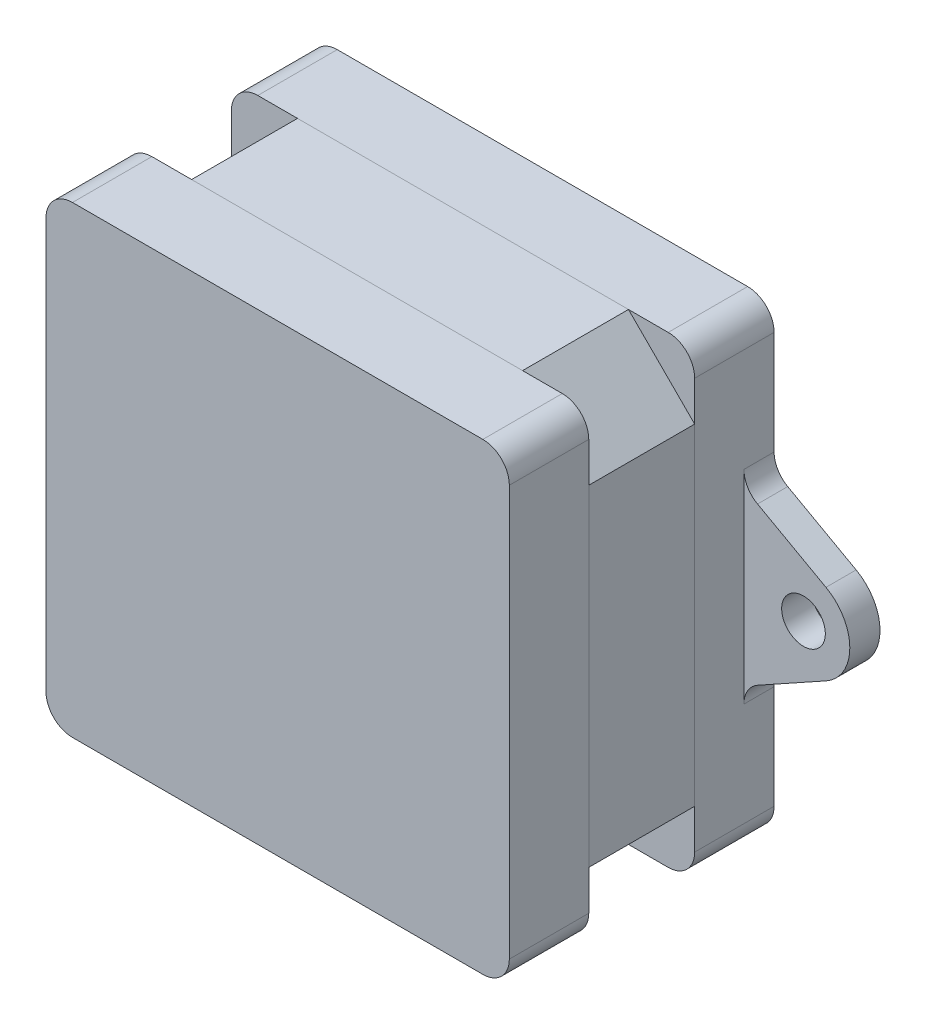
SolidWorks part; units mm, degrees
ref_plane "Front Plane" through (0, 0, 0) normal (0, 0, 1) x (1, 0, 0)
ref_plane "Top Plane" through (0, 0, 0) normal (0, 1, 0) x (1, 0, 0)
ref_plane "Right Plane" through (0, 0, 0) normal (1, 0, 0) x (0, 0, -1)
sketch "Sketch1" plane through (0, 0, 0) normal (0, 0, 1) x (1, 0, 0)
  line L1 (-15.5189, 15.7665) -> (19.4811, 15.7665)
  line L2 (-15.5189, 15.7665) -> (-15.5189, -19.2335)
  line L3 (-15.5189, -19.2335) -> (19.4811, -19.2335)
  line L4 (19.4811, 15.7665) -> (19.4811, -19.2335)
  dimension "D1" = 35
  dimension "D2" = 35
extrude "Boss-Extrude1" add sketch "Sketch1" along normal blind 6
sketch "Sketch2" plane through (0, 0, 6) normal (0, 0, 1) x (1, 0, 0)
  line L0 (-10.5189, 15.7665) -> (-15.5189, 10.7665)
  line L1 (19.4811, 10.7665) -> (14.4811, 15.7665)
  line L2 (14.4811, -19.2335) -> (19.4811, -14.2335)
  line L3 (-15.5189, -14.2335) -> (-10.5189, -19.2335)
  line L4 (-15.5189, 15.7665) -> (-15.5189, -19.2335)
  line L5 (-15.5189, -19.2335) -> (19.4811, -19.2335)
  line L6 (19.4811, -19.2335) -> (19.4811, 15.7665)
  line L7 (19.4811, 15.7665) -> (-15.5189, 15.7665)
  line L8 (-15.5189, 10.7665) -> (-15.5189, -14.2335)
  line L9 (-10.5189, -19.2335) -> (14.4811, -19.2335)
  line L10 (19.4811, -14.2335) -> (19.4811, 10.7665)
  line L11 (14.4811, 15.7665) -> (-10.5189, 15.7665)
  dimension "D1" = 0
extrude "Boss-Extrude2" add sketch "Sketch2" along normal blind 8 separate body
sketch "Sketch3" plane through (0, 0, 14) normal (0, 0, 1) x (1, 0, 0)
  line L4 (-15.5189, 15.7665) -> (-15.5189, -19.2335)
  line L5 (-15.5189, -19.2335) -> (19.4811, -19.2335)
  line L6 (19.4811, -19.2335) -> (19.4811, 15.7665)
  line L7 (19.4811, 15.7665) -> (-15.5189, 15.7665)
  line L8 (-15.5189, 15.7665) -> (-15.5189, -19.2335)
  line L9 (-15.5189, -19.2335) -> (19.4811, -19.2335)
  line L10 (19.4811, -19.2335) -> (19.4811, 15.7665)
  line L11 (19.4811, 15.7665) -> (-15.5189, 15.7665)
  dimension "D1" = 0
extrude "Boss-Extrude3" add sketch "Sketch3" along normal blind 6 separate body
hole_wizard "M3 Tapped Hole1" positions "Sketch5" profile "Sketch4" tap size "M3" standard "DIN"
sketch "Sketch5" plane through (0, 0, 0) normal (0, 0, -1) x (-1, 0, 0)
  line L0 (-19.4811, -19.2335) -> (-19.4811, 15.7665) construction
  line L1 (-19.4811, 15.7665) -> (15.5189, 15.7665) construction
  point P0 (-15.2311, 11.5165)
  point P2 (11.2689, 11.5165)
  point P4 (11.2689, -14.9835)
  point P6 (-15.2311, -14.9835)
  dimension "D1" = 26.5
  dimension "D2" = 26.5
  dimension "D3" = 4.25
  dimension "D4" = 4.25
sketch "Sketch4" plane through (15.2311, 11.5165, 0) normal (1, 0, 0) x (0, 1, 0)
  line L0 (0, 0) -> (0, 8.2511)
  line L1 (0, 8.2511) -> (1.25, 7.5)
  line L2 (1.25, 7.5) -> (1.25, 0)
  line L5 (1.25, 0) -> (0, 0)
  line L10 (0, 8.2511) -> (-1.25, 7.5) construction
  line L11 (0, -6.35) -> (0, 107.95) construction
  dimension "Tap Drill Dia." = 2.5
  dimension "Tap Drill Depth" = 7.5
  dimension "Drill Angle" = 118
cosmetic thread "Hole Thread1" parameters "D1"=6, "D2"=3
cosmetic thread "Hole Thread2" parameters "D1"=6, "D2"=3
cosmetic thread "Hole Thread3" parameters "D1"=6, "D2"=3
cosmetic thread "Hole Thread4" parameters "D1"=6, "D2"=3
fillet "Fillet1" radius 2 4 edges at (-15.5189, 15.7665, 3) (-15.5189, -19.2335, 3) (19.4811, -19.2335, 3) (19.4811, 15.7665, 3)
fillet "Fillet2" radius 2 4 edges at (19.4811, -19.2335, 17) (19.4811, 15.7665, 17) (-15.5189, -19.2335, 17) (-15.5189, 15.7665, 17)
sketch "Sketch6" plane through (0, 0, 0) normal (0, 0, -1) x (-1, 0, 0)
  line L0 (-19.4811, -17.2335) -> (-19.4811, 13.7665) construction
  line L1 (-17.4811, 15.7665) -> (13.5189, 15.7665) construction
  circle A0 centre (-1.9811, -1.7335) radius 11
  circle A1 centre (-1.9811, -1.7335) radius 4
  point P2 (-19.4811, -1.7335)
  dimension "D1" = 17.5
  dimension "D2" = 17.5
extrude "Boss-Extrude4" add sketch "Sketch6" along normal blind 2 contours A0
fillet "Fillet3" radius 0.5 1 edges at (-9.0189, -1.7335, -2)
sketch "Sketch7" plane through (0, 0, 0) normal (0, 0, -1) x (-1, 0, 0)
  circle A0 centre (-1.9811, -1.7335) radius 2.5
  dimension "D1" = 5
extrude "Boss-Extrude5" add sketch "Sketch7" along normal blind 8.5 separate body
sketch "Sketch8" plane through (0, 0, -8.5) normal (0, 0, -1) x (-1, 0, 0)
  line L0 (-1.9811, 2.1665) -> (-1.9811, 2.8415)
  line L1 (-1.3018, 2.1069) -> (-1.1842, 2.7716)
  line L2 (-0.289, 1.7803) -> (0.0039, 2.3884)
  line L3 (0.2972, 1.4318) -> (0.6916, 1.9796)
  line L4 (1.068, 0.6981) -> (1.5957, 1.119)
  line L5 (1.445, 0.1298) -> (2.0379, 0.4523)
  line L6 (1.8211, -0.8657) -> (2.4792, -0.7155)
  line L7 (1.9141, -1.5412) -> (2.5883, -1.508)
  line L8 (1.8211, -2.6013) -> (2.4792, -2.7515)
  line L9 (1.6118, -3.2504) -> (2.2336, -3.5129)
  line L10 (1.068, -4.1651) -> (1.5957, -4.586)
  line L11 (0.5978, -4.6591) -> (1.0442, -5.1654)
  line L12 (-0.289, -5.2473) -> (0.0039, -5.8554)
  line L13 (-0.9269, -5.4883) -> (-0.7445, -6.1382)
  line L14 (-1.9811, -5.6335) -> (-1.9811, -6.3085)
  line L15 (-2.6605, -5.5739) -> (-2.7781, -6.2385)
  line L16 (-3.6733, -5.2473) -> (-3.9662, -5.8554)
  line L17 (-4.2595, -4.8988) -> (-4.6538, -5.4466)
  line L18 (-5.0303, -4.1651) -> (-5.558, -4.586)
  line L19 (-5.4072, -3.5968) -> (-6.0002, -3.9193)
  line L20 (-5.7834, -2.6013) -> (-6.4414, -2.7515)
  line L21 (-5.8764, -1.9257) -> (-6.5506, -1.959)
  line L22 (-5.7834, -0.8657) -> (-6.4414, -0.7155)
  line L23 (-5.574, -0.2166) -> (-6.1959, 0.0459)
  line L24 (-5.0303, 0.6981) -> (-5.558, 1.119)
  line L25 (-4.5601, 1.1921) -> (-5.0064, 1.6984)
  line L26 (-3.6733, 1.7803) -> (-3.9662, 2.3884)
  line L27 (-3.0353, 2.0213) -> (-3.2178, 2.6712)
  arc A0 (-1.9811, 2.1665) -> (-3.0353, 2.0213) centre (-1.9811, -1.7335) ccw
  arc A1 (-0.289, 1.7803) -> (-1.3018, 2.1069) centre (-1.9811, -1.7335) ccw
  arc A2 (-1.1842, 2.7716) -> (-1.9811, 2.8415) centre (-1.9811, -1.7335) ccw
  arc A3 (0.6916, 1.9796) -> (0.0039, 2.3884) centre (-1.9811, -1.7335) ccw
  arc A4 (1.068, 0.6981) -> (0.2972, 1.4318) centre (-1.9811, -1.7335) ccw
  arc A5 (1.8211, -0.8657) -> (1.445, 0.1298) centre (-1.9811, -1.7335) ccw
  arc A6 (2.0379, 0.4523) -> (1.5957, 1.119) centre (-1.9811, -1.7335) ccw
  arc A7 (2.5883, -1.508) -> (2.4792, -0.7155) centre (-1.9811, -1.7335) ccw
  arc A8 (1.8211, -2.6013) -> (1.9141, -1.5412) centre (-1.9811, -1.7335) ccw
  arc A9 (2.2336, -3.5129) -> (2.4792, -2.7515) centre (-1.9811, -1.7335) ccw
  arc A10 (1.068, -4.1651) -> (1.6118, -3.2504) centre (-1.9811, -1.7335) ccw
  arc A11 (1.0442, -5.1654) -> (1.5957, -4.586) centre (-1.9811, -1.7335) ccw
  arc A12 (-0.289, -5.2473) -> (0.5978, -4.6591) centre (-1.9811, -1.7335) ccw
  arc A13 (-1.9811, -5.6335) -> (-0.9269, -5.4883) centre (-1.9811, -1.7335) ccw
  arc A14 (-0.7445, -6.1382) -> (0.0039, -5.8554) centre (-1.9811, -1.7335) ccw
  arc A15 (-2.7781, -6.2385) -> (-1.9811, -6.3085) centre (-1.9811, -1.7335) ccw
  arc A16 (-3.6733, -5.2473) -> (-2.6605, -5.5739) centre (-1.9811, -1.7335) ccw
  arc A17 (-4.6538, -5.4466) -> (-3.9662, -5.8554) centre (-1.9811, -1.7335) ccw
  arc A18 (-5.0303, -4.1651) -> (-4.2595, -4.8988) centre (-1.9811, -1.7335) ccw
  arc A19 (-6.0002, -3.9193) -> (-5.558, -4.586) centre (-1.9811, -1.7335) ccw
  arc A20 (-5.7834, -2.6013) -> (-5.4072, -3.5968) centre (-1.9811, -1.7335) ccw
  arc A21 (-6.5506, -1.959) -> (-6.4414, -2.7515) centre (-1.9811, -1.7335) ccw
  arc A22 (-5.7834, -0.8657) -> (-5.8764, -1.9257) centre (-1.9811, -1.7335) ccw
  arc A23 (-6.1959, 0.0459) -> (-6.4414, -0.7155) centre (-1.9811, -1.7335) ccw
  arc A24 (-5.0303, 0.6981) -> (-5.574, -0.2166) centre (-1.9811, -1.7335) ccw
  arc A25 (-5.0064, 1.6984) -> (-5.558, 1.119) centre (-1.9811, -1.7335) ccw
  arc A26 (-3.6733, 1.7803) -> (-4.5601, 1.1921) centre (-1.9811, -1.7335) ccw
  arc A27 (-3.2178, 2.6712) -> (-3.9662, 2.3884) centre (-1.9811, -1.7335) ccw
  circle A28 centre (-1.9811, -1.7335) radius 2.5
  point P61 (-1.9811, -1.7335)
  dimension "D1" = 9.15
  dimension "D2" = 7.8
  dimension "D3" = 0.8
  dimension "D4" = 14
extrude "Boss-Extrude6" add sketch "Sketch8" against normal blind 5.5 separate body
sketch "Sketch9" plane through (0, 0, 0) normal (0, 0, -1) x (-1, 0, 0)
  line L0 (-19.4811, 4.7665) -> (-19.4811, -8.2335)
  line L1 (-19.4811, -17.2335) -> (-19.4811, 13.7665) construction
  line L2 (-19.4811, 4.7665) -> (-25.6794, 1.3269)
  line L3 (-19.4811, -8.2335) -> (-25.6794, -4.7938)
  line L4 (-1.9811, 15.7665) -> (-1.9811, -19.2335) construction
  line L5 (-17.4811, 15.7665) -> (13.5189, 15.7665) construction
  line L6 (13.5189, -19.2335) -> (-17.4811, -19.2335) construction
  line L7 (15.5189, -8.2335) -> (21.7172, -4.7938)
  line L8 (15.5189, 4.7665) -> (21.7172, 1.3269)
  line L9 (15.5189, 4.7665) -> (15.5189, -8.2335)
  line L10 (-19.4811, -1.7335) -> (15.5189, -1.7335) construction
  circle A0 centre (-23.9811, -1.7335) radius 1.65
  circle A1 centre (-1.9811, -1.7335) radius 2.5 construction
  arc A2 (-25.6794, 1.3269) -> (-25.6794, -4.7938) centre (-23.9811, -1.7335) ccw
  arc A3 (21.7172, 1.3269) -> (21.7172, -4.7938) centre (20.0189, -1.7335) cw
  circle A4 centre (20.0189, -1.7335) radius 1.65
  dimension "D3" = 3.3
  dimension "D1" = 3.5
  dimension "D2" = 13
  dimension "D4" = 22
  dimension "D5" = 6.5
extrude "Boss-Extrude7" add sketch "Sketch9" against normal blind 2.28
fillet "Fillet4" radius 2 4 edges at (19.4811, -8.2335, 1.14) (19.4811, 4.7665, 1.14) (-15.5189, 4.7665, 1.14) (-15.5189, -8.2335, 1.14)
